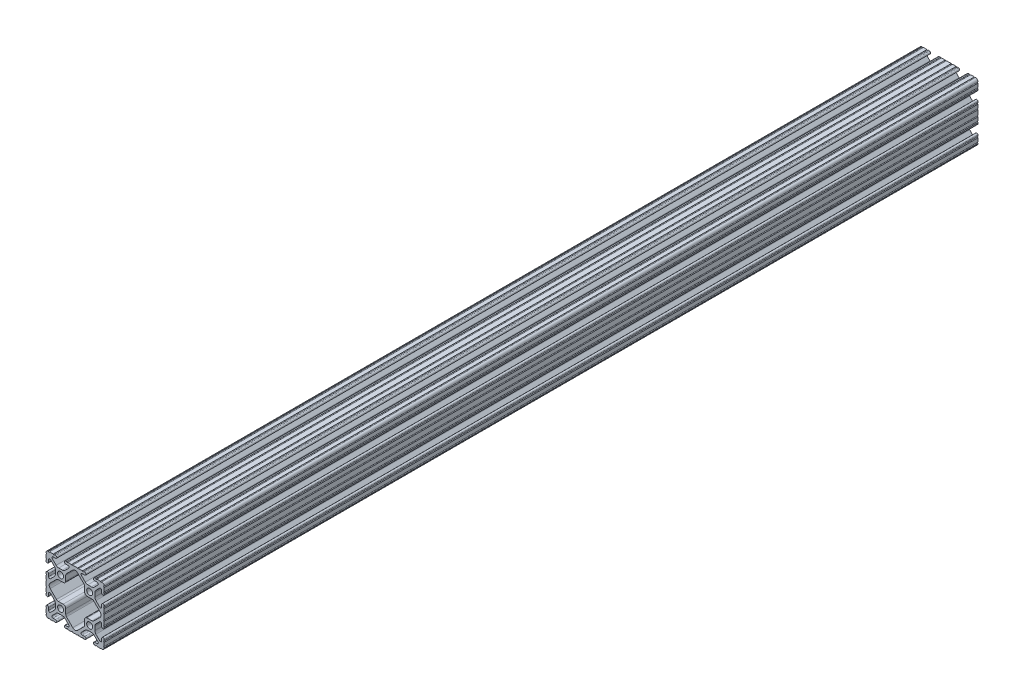
SolidWorks part; units mm, degrees
material "6063-T6"
ref_plane "Front Plane" through (0, 0, 0) normal (0, 0, 1) x (1, 0, 0)
ref_plane "Top Plane" through (0, 0, 0) normal (0, 1, 0) x (1, 0, 0)
ref_plane "Right Plane" through (0, 0, 0) normal (1, 0, 0) x (0, 0, -1)
sketch "Sketch1" plane through (0, 0, 0) normal (0, 0, 1) x (1, 0, 0)
  line L0 (-10.4013, 8.1915) -> (-14.7306, 8.1915)
  line L1 (-16.2932, 7.5443) -> (-21.772, 2.0655)
  line L2 (-21.772, -2.0655) -> (-16.2932, -7.5443)
  line L3 (-14.7306, -8.1915) -> (-10.4013, -8.1915)
  line L4 (-8.1915, -10.4013) -> (-8.1915, -14.7306)
  line L5 (-7.5443, -16.2932) -> (-2.0655, -21.772)
  line L6 (2.0655, -21.772) -> (7.5443, -16.2932)
  line L7 (8.1915, -14.7306) -> (8.1915, -10.4013)
  line L8 (10.4013, -8.1915) -> (14.7306, -8.1915)
  line L9 (16.2932, -7.5443) -> (21.772, -2.0655)
  line L10 (21.772, 2.0655) -> (16.2932, 7.5443)
  line L11 (14.7306, 8.1915) -> (10.4013, 8.1915)
  line L12 (8.1915, 10.4013) -> (8.1915, 14.7306)
  line L13 (7.5443, 16.2932) -> (2.0655, 21.772)
  line L14 (-2.0655, 21.772) -> (-7.5443, 16.2932)
  line L15 (-8.1915, 14.7306) -> (-8.1915, 10.4013)
  line L16 (-2.1336, -25.4) -> (2.1336, -25.4)
  line L17 (3.1496, -25.4) -> (6.3754, -25.4)
  line L18 (7.3914, -25.4) -> (8.3439, -25.4)
  line L19 (8.3439, -23.1902) -> (6.2252, -23.1902)
  line L20 (5.5068, -21.4558) -> (8.8241, -18.1384)
  line L21 (11.0692, -17.2085) -> (14.3308, -17.2085)
  line L22 (16.5759, -18.1384) -> (19.8932, -21.4558)
  line L23 (19.1748, -23.1902) -> (17.0561, -23.1902)
  line L24 (17.0561, -25.4) -> (18.0086, -25.4)
  line L25 (19.0246, -25.4) -> (22.2504, -25.4)
  line L26 (23.2664, -25.4) -> (23.2918, -25.4)
  line L27 (25.4, -23.2918) -> (25.4, -23.2664)
  line L28 (25.4, -22.2504) -> (25.4, -19.0246)
  line L29 (25.4, -18.0086) -> (25.4, -17.0561)
  line L30 (23.1902, -17.0561) -> (23.1902, -19.1748)
  line L31 (21.4558, -19.8932) -> (18.1384, -16.5759)
  line L32 (17.2085, -14.3308) -> (17.2085, -11.0692)
  line L33 (18.1384, -8.8241) -> (21.4558, -5.5068)
  line L34 (23.1902, -6.2252) -> (23.1902, -8.3439)
  line L35 (25.4, -8.3439) -> (25.4, -7.3914)
  line L36 (25.4, -6.3754) -> (25.4, -3.1496)
  line L37 (25.4, -2.1336) -> (25.4, 2.1336)
  line L38 (25.4, 3.1496) -> (25.4, 6.3754)
  line L39 (25.4, 7.3914) -> (25.4, 8.3439)
  line L40 (23.1902, 8.3439) -> (23.1902, 6.2252)
  line L41 (21.4558, 5.5068) -> (18.1384, 8.8241)
  line L42 (17.2085, 11.0692) -> (17.2085, 14.3308)
  line L43 (18.1384, 16.5759) -> (21.4558, 19.8932)
  line L44 (23.1902, 19.1748) -> (23.1902, 17.0561)
  line L45 (25.4, 17.0561) -> (25.4, 18.0086)
  line L46 (25.4, 19.0246) -> (25.4, 22.2504)
  line L47 (25.4, 23.2664) -> (25.4, 23.2918)
  line L48 (23.2918, 25.4) -> (23.2664, 25.4)
  line L49 (22.2504, 25.4) -> (19.0246, 25.4)
  line L50 (18.0086, 25.4) -> (17.0561, 25.4)
  line L51 (17.0561, 23.1902) -> (19.1748, 23.1902)
  line L52 (19.8932, 21.4558) -> (16.5759, 18.1384)
  line L53 (14.3308, 17.2085) -> (11.0692, 17.2085)
  line L54 (8.8241, 18.1384) -> (5.5068, 21.4558)
  line L55 (6.2252, 23.1902) -> (8.3439, 23.1902)
  line L56 (8.3439, 25.4) -> (7.3914, 25.4)
  line L57 (6.3754, 25.4) -> (3.1496, 25.4)
  line L58 (2.1336, 25.4) -> (-2.1336, 25.4)
  line L59 (-3.1496, 25.4) -> (-6.3754, 25.4)
  line L60 (-7.3914, 25.4) -> (-8.3439, 25.4)
  line L61 (-8.3439, 23.1902) -> (-6.2252, 23.1902)
  line L62 (-5.5068, 21.4558) -> (-8.8241, 18.1384)
  line L63 (-11.0692, 17.2085) -> (-14.3308, 17.2085)
  line L64 (-16.5759, 18.1384) -> (-19.8932, 21.4558)
  line L65 (-19.1748, 23.1902) -> (-17.0561, 23.1902)
  line L66 (-17.0561, 25.4) -> (-18.0086, 25.4)
  line L67 (-19.0246, 25.4) -> (-22.2504, 25.4)
  line L68 (-23.2664, 25.4) -> (-23.2918, 25.4)
  line L69 (-25.4, 23.2918) -> (-25.4, 23.2664)
  line L70 (-25.4, 22.2504) -> (-25.4, 19.0246)
  line L71 (-25.4, 18.0086) -> (-25.4, 17.0561)
  line L72 (-23.1902, 17.0561) -> (-23.1902, 19.1748)
  line L73 (-21.4558, 19.8932) -> (-18.1384, 16.5759)
  line L74 (-17.2085, 14.3308) -> (-17.2085, 11.0692)
  line L75 (-18.1384, 8.8241) -> (-21.4558, 5.5068)
  line L76 (-23.1902, 6.2252) -> (-23.1902, 8.3439)
  line L77 (-25.4, 8.3439) -> (-25.4, 7.3914)
  line L78 (-25.4, 6.3754) -> (-25.4, 3.1496)
  line L79 (-25.4, 2.1336) -> (-25.4, -2.1336)
  line L80 (-25.4, -3.1496) -> (-25.4, -6.3754)
  line L81 (-25.4, -7.3914) -> (-25.4, -8.3439)
  line L82 (-23.1902, -8.3439) -> (-23.1902, -6.2252)
  line L83 (-21.4558, -5.5068) -> (-18.1384, -8.8241)
  line L84 (-17.2085, -11.0692) -> (-17.2085, -14.3308)
  line L85 (-18.1384, -16.5759) -> (-21.4558, -19.8932)
  line L86 (-23.1902, -19.1748) -> (-23.1902, -17.0561)
  line L87 (-25.4, -17.0561) -> (-25.4, -18.0086)
  line L88 (-25.4, -19.0246) -> (-25.4, -22.2504)
  line L89 (-25.4, -23.2664) -> (-25.4, -23.2918)
  line L90 (-23.2918, -25.4) -> (-23.2664, -25.4)
  line L91 (-22.2504, -25.4) -> (-19.0246, -25.4)
  line L92 (-18.0086, -25.4) -> (-17.0561, -25.4)
  line L93 (-17.0561, -23.1902) -> (-19.1748, -23.1902)
  line L94 (-19.8932, -21.4558) -> (-16.5759, -18.1384)
  line L95 (-14.3308, -17.2085) -> (-11.0692, -17.2085)
  line L96 (-8.8241, -18.1384) -> (-5.5068, -21.4558)
  line L97 (-6.2252, -23.1902) -> (-8.3439, -23.1902)
  line L98 (-8.3439, -25.4) -> (-7.3914, -25.4)
  line L99 (-6.3754, -25.4) -> (-3.1496, -25.4)
  arc A0 (-14.7306, 8.1915) -> (-16.2932, 7.5443) centre (-14.7306, 5.9817) ccw
  arc A1 (-21.772, 2.0655) -> (-21.772, -2.0655) centre (-19.7065, 0) ccw
  arc A2 (-16.2932, -7.5443) -> (-14.7306, -8.1915) centre (-14.7306, -5.9817) ccw
  arc A3 (-8.1915, -10.4013) -> (-10.4013, -8.1915) centre (-10.4013, -10.4013) ccw
  arc A4 (-8.1915, -14.7306) -> (-7.5443, -16.2932) centre (-5.9817, -14.7306) ccw
  arc A5 (-2.0655, -21.772) -> (2.0655, -21.772) centre (0, -19.7065) ccw
  arc A6 (7.5443, -16.2932) -> (8.1915, -14.7306) centre (5.9817, -14.7306) ccw
  arc A7 (10.4013, -8.1915) -> (8.1915, -10.4013) centre (10.4013, -10.4013) ccw
  arc A8 (14.7306, -8.1915) -> (16.2932, -7.5443) centre (14.7306, -5.9817) ccw
  arc A9 (21.772, -2.0655) -> (21.772, 2.0655) centre (19.7065, 0) ccw
  arc A10 (16.2932, 7.5443) -> (14.7306, 8.1915) centre (14.7306, 5.9817) ccw
  arc A11 (8.1915, 10.4013) -> (10.4013, 8.1915) centre (10.4013, 10.4013) ccw
  arc A12 (8.1915, 14.7306) -> (7.5443, 16.2932) centre (5.9817, 14.7306) ccw
  arc A13 (2.0655, 21.772) -> (-2.0655, 21.772) centre (0, 19.7065) ccw
  arc A14 (-7.5443, 16.2932) -> (-8.1915, 14.7306) centre (-5.9817, 14.7306) ccw
  arc A15 (-10.4013, 8.1915) -> (-8.1915, 10.4013) centre (-10.4013, 10.4013) ccw
  arc A16 (-2.1336, -25.4) -> (-3.1496, -25.4) centre (-2.6416, -25.4) ccw
  arc A17 (3.1496, -25.4) -> (2.1336, -25.4) centre (2.6416, -25.4) ccw
  arc A18 (7.3914, -25.4) -> (6.3754, -25.4) centre (6.8834, -25.4) ccw
  arc A19 (8.3439, -25.4) -> (8.3439, -23.1902) centre (8.3439, -24.2951) ccw
  arc A20 (5.5068, -21.4558) -> (6.2252, -23.1902) centre (6.2252, -22.1742) ccw
  arc A21 (11.0692, -17.2085) -> (8.8241, -18.1384) centre (11.0692, -20.3835) ccw
  arc A22 (16.5759, -18.1384) -> (14.3308, -17.2085) centre (14.3308, -20.3835) ccw
  arc A23 (19.1748, -23.1902) -> (19.8932, -21.4558) centre (19.1748, -22.1742) ccw
  arc A24 (17.0561, -23.1902) -> (17.0561, -25.4) centre (17.0561, -24.2951) ccw
  arc A25 (19.0246, -25.4) -> (18.0086, -25.4) centre (18.5166, -25.4) ccw
  arc A26 (23.2664, -25.4) -> (22.2504, -25.4) centre (22.7584, -25.4) ccw
  arc A27 (23.2918, -25.4) -> (25.4, -23.2918) centre (23.2918, -23.2918) ccw
  arc A28 (25.4, -22.2504) -> (25.4, -23.2664) centre (25.4, -22.7584) ccw
  arc A29 (25.4, -18.0086) -> (25.4, -19.0246) centre (25.4, -18.5166) ccw
  arc A30 (25.4, -17.0561) -> (23.1902, -17.0561) centre (24.2951, -17.0561) ccw
  arc A31 (21.4558, -19.8932) -> (23.1902, -19.1748) centre (22.1742, -19.1748) ccw
  arc A32 (17.2085, -14.3308) -> (18.1384, -16.5759) centre (20.3835, -14.3308) ccw
  arc A33 (18.1384, -8.8241) -> (17.2085, -11.0692) centre (20.3835, -11.0692) ccw
  arc A34 (23.1902, -6.2252) -> (21.4558, -5.5068) centre (22.1742, -6.2252) ccw
  arc A35 (23.1902, -8.3439) -> (25.4, -8.3439) centre (24.2951, -8.3439) ccw
  arc A36 (25.4, -6.3754) -> (25.4, -7.3914) centre (25.4, -6.8834) ccw
  arc A37 (25.4, -2.1336) -> (25.4, -3.1496) centre (25.4, -2.6416) ccw
  arc A38 (25.4, 3.1496) -> (25.4, 2.1336) centre (25.4, 2.6416) ccw
  arc A39 (25.4, 7.3914) -> (25.4, 6.3754) centre (25.4, 6.8834) ccw
  arc A40 (25.4, 8.3439) -> (23.1902, 8.3439) centre (24.2951, 8.3439) ccw
  arc A41 (21.4558, 5.5068) -> (23.1902, 6.2252) centre (22.1742, 6.2252) ccw
  arc A42 (17.2085, 11.0692) -> (18.1384, 8.8241) centre (20.3835, 11.0692) ccw
  arc A43 (18.1384, 16.5759) -> (17.2085, 14.3308) centre (20.3835, 14.3308) ccw
  arc A44 (23.1902, 19.1748) -> (21.4558, 19.8932) centre (22.1742, 19.1748) ccw
  arc A45 (23.1902, 17.0561) -> (25.4, 17.0561) centre (24.2951, 17.0561) ccw
  arc A46 (25.4, 19.0246) -> (25.4, 18.0086) centre (25.4, 18.5166) ccw
  arc A47 (25.4, 23.2664) -> (25.4, 22.2504) centre (25.4, 22.7584) ccw
  arc A48 (25.4, 23.2918) -> (23.2918, 25.4) centre (23.2918, 23.2918) ccw
  arc A49 (22.2504, 25.4) -> (23.2664, 25.4) centre (22.7584, 25.4) ccw
  arc A50 (18.0086, 25.4) -> (19.0246, 25.4) centre (18.5166, 25.4) ccw
  arc A51 (17.0561, 25.4) -> (17.0561, 23.1902) centre (17.0561, 24.2951) ccw
  arc A52 (19.8932, 21.4558) -> (19.1748, 23.1902) centre (19.1748, 22.1742) ccw
  arc A53 (14.3308, 17.2085) -> (16.5759, 18.1384) centre (14.3308, 20.3835) ccw
  arc A54 (8.8241, 18.1384) -> (11.0692, 17.2085) centre (11.0692, 20.3835) ccw
  arc A55 (6.2252, 23.1902) -> (5.5068, 21.4558) centre (6.2252, 22.1742) ccw
  arc A56 (8.3439, 23.1902) -> (8.3439, 25.4) centre (8.3439, 24.2951) ccw
  arc A57 (6.3754, 25.4) -> (7.3914, 25.4) centre (6.8834, 25.4) ccw
  arc A58 (2.1336, 25.4) -> (3.1496, 25.4) centre (2.6416, 25.4) ccw
  arc A59 (-3.1496, 25.4) -> (-2.1336, 25.4) centre (-2.6416, 25.4) ccw
  arc A60 (-7.3914, 25.4) -> (-6.3754, 25.4) centre (-6.8834, 25.4) ccw
  arc A61 (-8.3439, 25.4) -> (-8.3439, 23.1902) centre (-8.3439, 24.2951) ccw
  arc A62 (-5.5068, 21.4558) -> (-6.2252, 23.1902) centre (-6.2252, 22.1742) ccw
  arc A63 (-11.0692, 17.2085) -> (-8.8241, 18.1384) centre (-11.0692, 20.3835) ccw
  arc A64 (-16.5759, 18.1384) -> (-14.3308, 17.2085) centre (-14.3308, 20.3835) ccw
  arc A65 (-19.1748, 23.1902) -> (-19.8932, 21.4558) centre (-19.1748, 22.1742) ccw
  arc A66 (-17.0561, 23.1902) -> (-17.0561, 25.4) centre (-17.0561, 24.2951) ccw
  arc A67 (-19.0246, 25.4) -> (-18.0086, 25.4) centre (-18.5166, 25.4) ccw
  arc A68 (-23.2664, 25.4) -> (-22.2504, 25.4) centre (-22.7584, 25.4) ccw
  arc A69 (-23.2918, 25.4) -> (-25.4, 23.2918) centre (-23.2918, 23.2918) ccw
  arc A70 (-25.4, 22.2504) -> (-25.4, 23.2664) centre (-25.4, 22.7584) ccw
  arc A71 (-25.4, 18.0086) -> (-25.4, 19.0246) centre (-25.4, 18.5166) ccw
  arc A72 (-25.4, 17.0561) -> (-23.1902, 17.0561) centre (-24.2951, 17.0561) ccw
  arc A73 (-21.4558, 19.8932) -> (-23.1902, 19.1748) centre (-22.1742, 19.1748) ccw
  arc A74 (-17.2085, 14.3308) -> (-18.1384, 16.5759) centre (-20.3835, 14.3308) ccw
  arc A75 (-18.1384, 8.8241) -> (-17.2085, 11.0692) centre (-20.3835, 11.0692) ccw
  arc A76 (-23.1902, 6.2252) -> (-21.4558, 5.5068) centre (-22.1742, 6.2252) ccw
  arc A77 (-23.1902, 8.3439) -> (-25.4, 8.3439) centre (-24.2951, 8.3439) ccw
  arc A78 (-25.4, 6.3754) -> (-25.4, 7.3914) centre (-25.4, 6.8834) ccw
  arc A79 (-25.4, 2.1336) -> (-25.4, 3.1496) centre (-25.4, 2.6416) ccw
  arc A80 (-25.4, -3.1496) -> (-25.4, -2.1336) centre (-25.4, -2.6416) ccw
  arc A81 (-25.4, -7.3914) -> (-25.4, -6.3754) centre (-25.4, -6.8834) ccw
  arc A82 (-25.4, -8.3439) -> (-23.1902, -8.3439) centre (-24.2951, -8.3439) ccw
  arc A83 (-21.4558, -5.5068) -> (-23.1902, -6.2252) centre (-22.1742, -6.2252) ccw
  arc A84 (-17.2085, -11.0692) -> (-18.1384, -8.8241) centre (-20.3835, -11.0692) ccw
  arc A85 (-18.1384, -16.5759) -> (-17.2085, -14.3308) centre (-20.3835, -14.3308) ccw
  arc A86 (-23.1902, -19.1748) -> (-21.4558, -19.8932) centre (-22.1742, -19.1748) ccw
  arc A87 (-23.1902, -17.0561) -> (-25.4, -17.0561) centre (-24.2951, -17.0561) ccw
  arc A88 (-25.4, -19.0246) -> (-25.4, -18.0086) centre (-25.4, -18.5166) ccw
  arc A89 (-25.4, -23.2664) -> (-25.4, -22.2504) centre (-25.4, -22.7584) ccw
  arc A90 (-25.4, -23.2918) -> (-23.2918, -25.4) centre (-23.2918, -23.2918) ccw
  arc A91 (-22.2504, -25.4) -> (-23.2664, -25.4) centre (-22.7584, -25.4) ccw
  arc A92 (-18.0086, -25.4) -> (-19.0246, -25.4) centre (-18.5166, -25.4) ccw
  arc A93 (-17.0561, -25.4) -> (-17.0561, -23.1902) centre (-17.0561, -24.2951) ccw
  arc A94 (-19.8932, -21.4558) -> (-19.1748, -23.1902) centre (-19.1748, -22.1742) ccw
  arc A95 (-14.3308, -17.2085) -> (-16.5759, -18.1384) centre (-14.3308, -20.3835) ccw
  arc A96 (-8.8241, -18.1384) -> (-11.0692, -17.2085) centre (-11.0692, -20.3835) ccw
  arc A97 (-6.2252, -23.1902) -> (-5.5068, -21.4558) centre (-6.2252, -22.1742) ccw
  arc A98 (-8.3439, -23.1902) -> (-8.3439, -25.4) centre (-8.3439, -24.2951) ccw
  arc A99 (-6.3754, -25.4) -> (-7.3914, -25.4) centre (-6.8834, -25.4) ccw
  circle A100 centre (12.7, 12.7) radius 2.6035
  circle A101 centre (12.7, -12.7) radius 2.6035
  circle A102 centre (-12.7, 12.7) radius 2.6035
  circle A103 centre (-12.7, -12.7) radius 2.6035
  dimension "D1" = 12.7
  dimension "D2" = 12.7
  dimension "D3" = 12.7
  dimension "D4" = 12.7
extrude "Extrude1" add sketch "Sketch1" along normal mid plane 762
